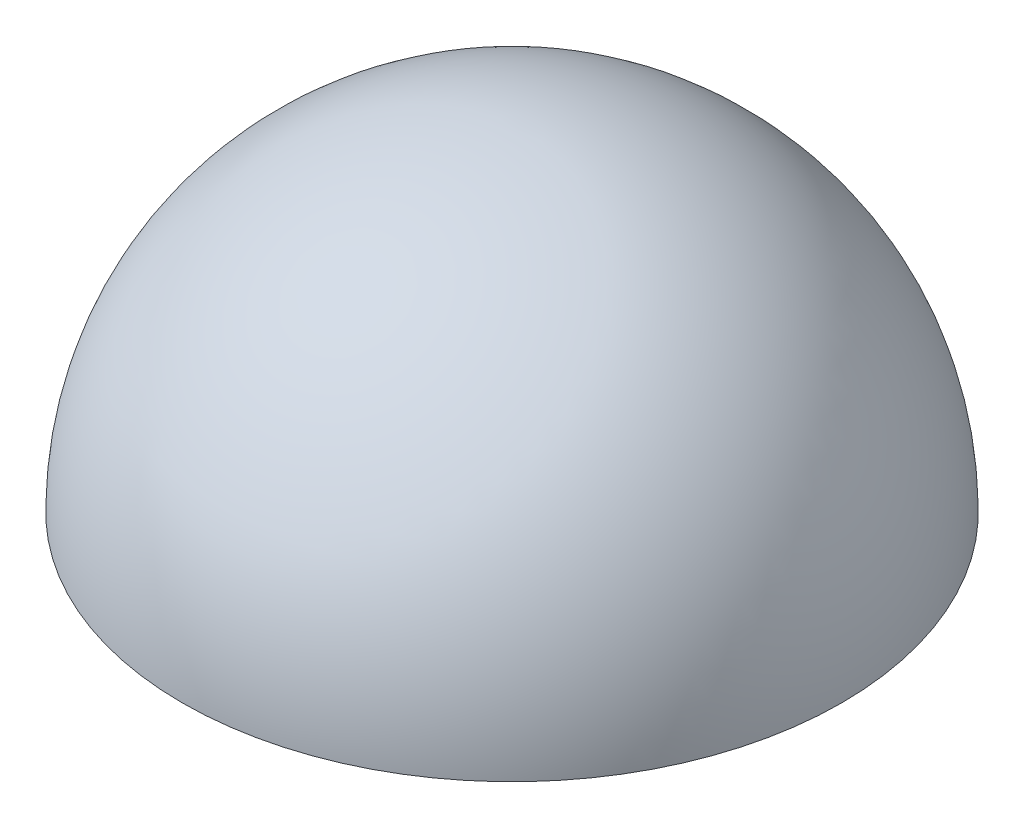
SolidWorks part; units mm, degrees
ref_plane "Front Plane" through (0, 0, 0) normal (0, 0, 1) x (1, 0, 0)
ref_plane "Top Plane" through (0, 0, 0) normal (0, 1, 0) x (1, 0, 0)
ref_plane "Right Plane" through (0, 0, 0) normal (1, 0, 0) x (0, 0, -1)
sketch "Sketch1" plane through (0, 0, 0) normal (0, 0, 1) x (1, 0, 0)
  line L0 (0, 2.7) -> (0, 0.15)
  line L1 (0, 0.15) -> (1.5, 0.15)
  line L2 (1.5, 0.15) -> (1.5, 0)
  line L3 (1.5, 0) -> (2.7, 0)
  line L4 (0, 0.15) -> (0, 0) construction
  arc A0 (0, 2.7) -> (2.7, 0) centre (0, 0) cw
  dimension "D1" = 2.7
  dimension "D2" = 2.7
  dimension "D3" = 0.15
  dimension "D4" = 1.5
revolve "Revolve1" add sketch "Sketch1" angle 360 about L0
